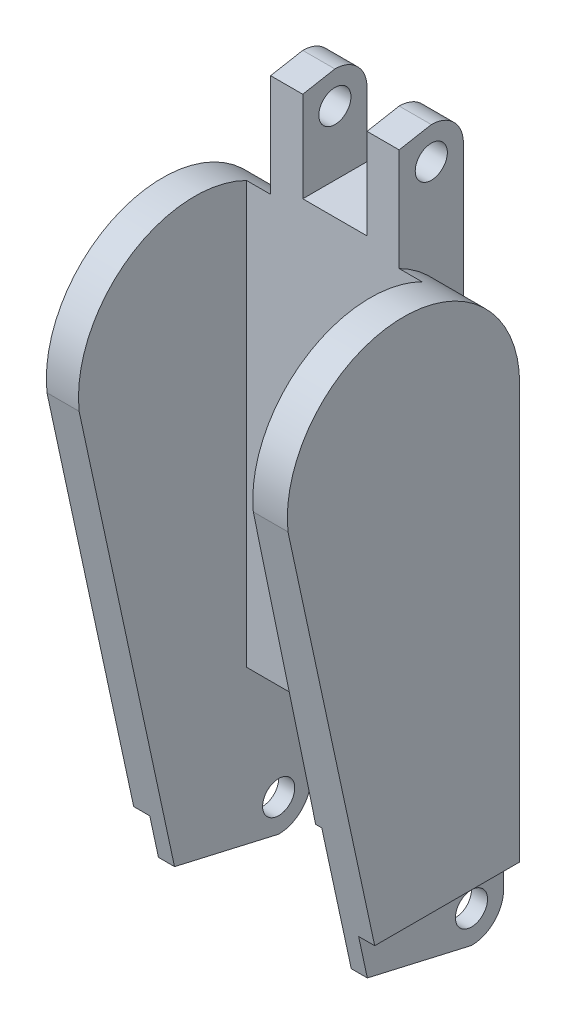
SolidWorks part; units mm, degrees
ref_plane "Front Plane" through (0, 0, 0) normal (1, 0, 0) x (0, 1, 0)
ref_plane "Top Plane" through (0, 0, 0) normal (0, 0, 1) x (0, 1, 0)
ref_plane "Right Plane" through (0, 0, 0) normal (0, 1, 0) x (-1, 0, 0)
sketch "Sketch2" plane through (0, 0, 0) normal (1, 0, 0) x (0, 1, 0)
  line L0 (0, -4) -> (-78, -4)
  line L1 (0, 0) -> (-5.35, 0) construction
  line L2 (-78, 0) -> (-78, 15) construction
  line L3 (-78, 15) -> (-76.5, 15) construction
  line L4 (-82, 0) -> (-78.4492, 15.448)
  line L5 (-74, 0) -> (-78, 0) construction
  line L7 (-76.5, 17) -> (-5.35, 33.4)
  line L8 (-1.35, 29.4) -> (4, 0)
  circle A0 centre (0, 0) radius 2
  arc A1 (0, -4) -> (4, 0) centre (0, 0) ccw
  circle A2 centre (-78, 0) radius 2
  arc A3 (-82, 0) -> (-78, -4) centre (-78, 0) ccw
  arc A4 (-76.5, 17) -> (-78.4492, 15.448) centre (-76.5, 15) ccw
  arc A5 (-1.35, 29.4) -> (-5.35, 33.4) centre (-5.35, 29.4) ccw
  dimension "D1" = 4
  dimension "D2" = 8
  dimension "D4" = 4
  dimension "D7" = 4
  dimension "D10" = 8
  dimension "D3" = 78
  dimension "D5" = 15
  dimension "D6" = 1.5
  dimension "D8" = 5.35
  dimension "D9" = 29.4
extrude "Boss-Extrude1" add sketch "Sketch2" along normal blind 30
ref_plane "Plane1" through (0, 0, 46) normal (0, 0, -1) x (-1, 0, 0)
sketch "Sketch3" plane through (0, 0, 46) normal (0, 0, -1) x (-1, 0, 0)
  line L0 (0, 0) -> (0, 4)
  line L1 (0, 0) -> (0, 4) construction
  line L2 (0, 4) -> (-7, 4)
  line L7 (-30, 4) -> (-30, 0) construction
  line L8 (-30, 4) -> (-30, -8)
  line L9 (-30, -78) -> (-30, 0) construction
  line L17 (0, -8) -> (0, 0)
  line L18 (-30, 4) -> (-23, 4)
  line L20 (-19, 4) -> (-11, 4)
  line L22 (-23, 4) -> (-23, -8)
  line L24 (-19, -8) -> (-11, -8)
  line L25 (-7, -8) -> (0, -8)
  line L26 (-30, -8) -> (-23, -8)
  line L27 (-19, 4) -> (-19, -8)
  line L28 (-11, 4) -> (-11, -8)
  line L29 (-7, 4) -> (-7, -8)
  dimension "D1" = 12
  dimension "D2" = 7
  dimension "D3" = 4
  dimension "D4" = 8
  dimension "D5" = 4
extrude "Cut-Extrude1" cut sketch "Sketch3" along normal blind 60
sketch "Sketch4" plane through (0, 0, 46) normal (0, 0, -1) x (-1, 0, 0)
  line L8 (-26, 3.9367) -> (-4, 3.9367) construction
  line L10 (-4, -82) -> (-25.0123, -82) construction
  line L12 (-15, 3.9367) -> (-4, 3.9367)
  line L13 (-15, 3.9367) -> (-26, 3.9367)
  line L14 (-26, 3.9367) -> (-25.0116, -82.0633)
  line L15 (-25.0116, -82.0633) -> (-4, -82.0633)
  line L16 (-4, 3.9367) -> (-4, -82.0633)
  dimension "D1" = 11
  dimension "D2" = 11
  dimension "D3" = 86
extrude "Cut-Extrude2" cut sketch "Sketch4" along normal blind 42
sketch "Sketch6" plane through (0, 0, 46) normal (0, 0, -1) x (-1, 0, 0)
  line L1 (-15, -62) -> (-4, -62)
  line L2 (-26, -62) -> (-26, -102)
  line L3 (-26, -102) -> (-4, -102)
  line L9 (-4, -102) -> (-4, -62)
  line L11 (-15, -62) -> (-26, -62)
  dimension "D1" = 40
  dimension "D2" = 11
  dimension "D3" = 11
extrude "Cut-Extrude5" cut sketch "Sketch6" along normal blind 70
sketch "Sketch7" plane through (0, 0, 0) normal (-1, 0, 0) x (0, -1, 0)
  line L1 (8, -4) -> (8, 32.7892) construction
  line L2 (8, 28.29) -> (8, 32.7892)
  line L3 (8, 32.7892) -> (76.5, 17)
  line L4 (8, 28.29) -> (79.0206, 12.962)
  line L6 (78.4492, 15.448) -> (82, 0) construction
  line L8 (78.4492, 15.448) -> (79.0206, 12.962)
  arc A1 (78.4492, 15.448) -> (76.5, 17) centre (76.5, 15) ccw
extrude "Cut-Extrude9" cut sketch "Sketch7" against normal blind 70
sketch "Sketch8" plane through (0, 0, 0) normal (-1, 0, 0) x (0, -1, 0)
  line L0 (8, -4) -> (8, 28.29) construction
  line L1 (8, -4) -> (22.46, -4) construction
  line L2 (78, -4) -> (8, -4) construction
  line L3 (22.46, -4) -> (22.46, 10.46) construction
  line L4 (8, 28.29) -> (25.4458, 24.6084)
  line L5 (22.46, -4) -> (-8.041, -4)
  line L6 (-8.041, -4) -> (-8.041, 32.9361)
  line L7 (-8.041, 32.9361) -> (8, 28.29)
  arc A0 (25.4458, 24.6084) -> (22.46, -4) centre (22.46, 10.46) ccw
  dimension "D1" = 14.46
  dimension "D2" = 14.46
extrude "Cut-Extrude10" cut sketch "Sketch8" against normal blind 7
ref_plane "Plane2" through (15, 0, 0) normal (1, 0, 0) x (0, 1, 0)
mirror "Mirror1" about plane through (15, 0, 0) normal (1, 0, 0) of "Cut-Extrude10"
sketch "Sketch9" plane through (0, 0, 0) normal (0, 0, 1) x (0, 1, 0)
  line L0 (-82, 0) -> (-82, -2)
  line L1 (-79.0206, 0) -> (-82, 0) construction
  line L2 (-82, -2) -> (-74, -2)
  line L3 (-82, 0) -> (-74, 0)
  line L4 (-23.9912, 0) -> (-79.0206, 0) construction
  line L5 (-74, 0) -> (-74, -2)
  line L6 (-82, -30) -> (-82, -28)
  line L7 (-79.0206, -30) -> (-82, -30) construction
  line L8 (-82, -28) -> (-74, -28)
  line L9 (-74, -28) -> (-74, -30)
  line L10 (-79.0206, -30) -> (-23.9912, -30) construction
  line L11 (-74, -30) -> (-82, -30)
  dimension "D1" = 2
  dimension "D2" = 8
  dimension "D3" = 2
extrude "Cut-Extrude11" cut sketch "Sketch9" against normal blind 17 and the other way blind 17 contours L5 L2 L0 L3 | L11 L6 L8 L9
